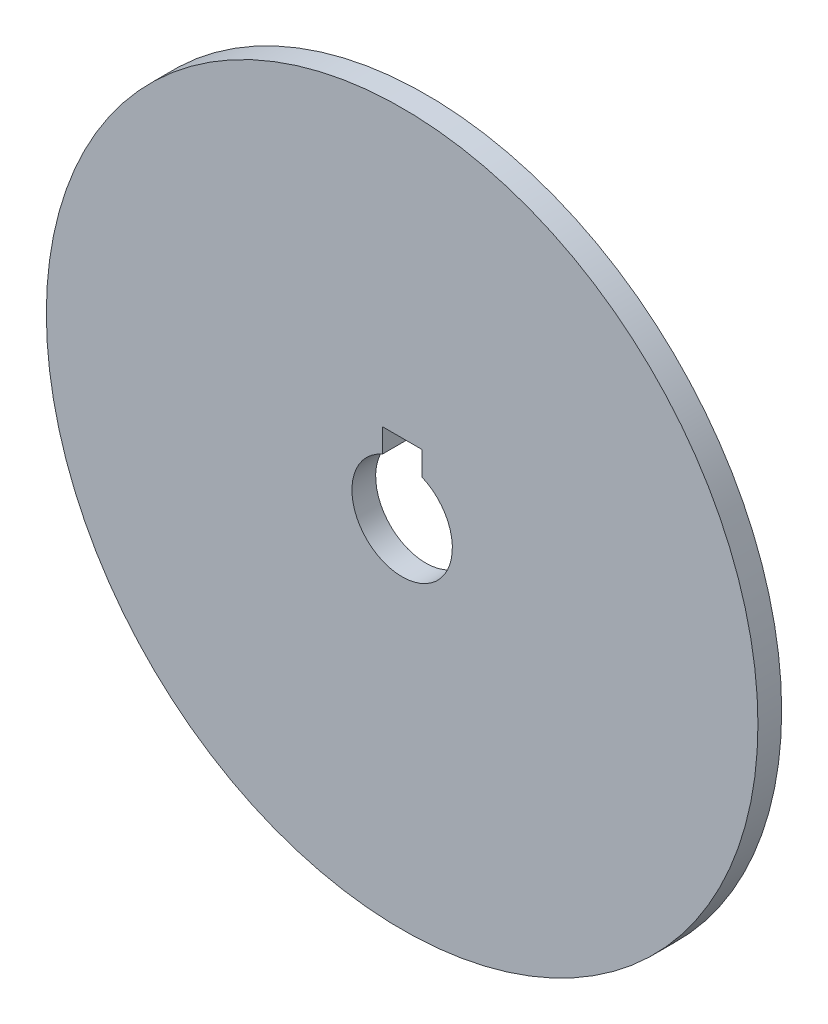
SolidWorks part; units mm, degrees
ref_plane "Alzado" through (0, 0, 0) normal (0, 0, 1) x (1, 0, 0)
ref_plane "Planta" through (0, 0, 0) normal (0, 1, 0) x (1, 0, 0)
ref_plane "Vista lateral" through (0, 0, 0) normal (1, 0, 0) x (0, 0, -1)
sketch "Croquis1" plane through (0, 0, 0) normal (0, 0, 1) x (1, 0, 0)
  line L2 (2.5, 5.8372) -> (2.5, 8.85)
  line L3 (2.5, 8.85) -> (-2.5, 8.85)
  line L4 (-2.5, 5.8372) -> (-2.5, 8.85)
  circle A0 centre (0, 0) radius 45
  arc A1 (-2.5, 5.8372) -> (2.5, 5.8372) centre (0, 0) ccw
  point P4 (0, 6.35)
  dimension "D1" = 12.7
  dimension "D3" = 90
  dimension "D2" = 5
extrude "Saliente-Extruir1" add sketch "Croquis1" along normal blind 3
